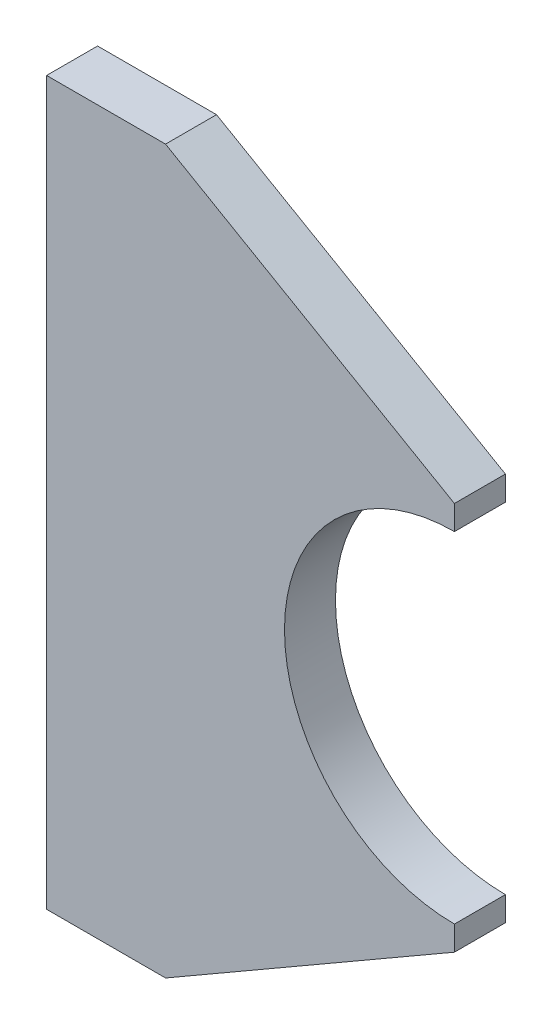
SolidWorks part; units mm, degrees
material "S45C"
ref_plane "Front Plane" through (0, 0, 0) normal (0, 0, 1) x (1, 0, 0)
ref_plane "Top Plane" through (0, 0, 0) normal (0, 1, 0) x (1, 0, 0)
ref_plane "Right Plane" through (0, 0, 0) normal (1, 0, 0) x (0, 0, -1)
sketch "Sketch1" plane through (0, 0, 0) normal (0, 0, 1) x (1, 0, 0)
  line L0 (0, 0) -> (-48, 0) construction
  line L1 (-48, -42.5) -> (-48, 42.5)
  line L2 (-48, 42.5) -> (-34, 42.5)
  line L3 (-34, 42.5) -> (0, 22.8701)
  line L4 (-34, -42.5) -> (0, -22.8701)
  line L5 (-48, -42.5) -> (-34, -42.5)
  line L6 (0, 20) -> (0, 22.8701)
  line L7 (0, -20) -> (0, -22.8701)
  arc A0 (0, 20) -> (0, -20) centre (0, 0) ccw
  dimension "D1" = 85
  dimension "D3" = 40
  dimension "D2" = 48
  dimension "D4" = 60
  dimension "D5" = 14
  dimension "D6" = 2.8701
extrude "Boss-Extrude1" add sketch "Sketch1" along normal mid plane 6
